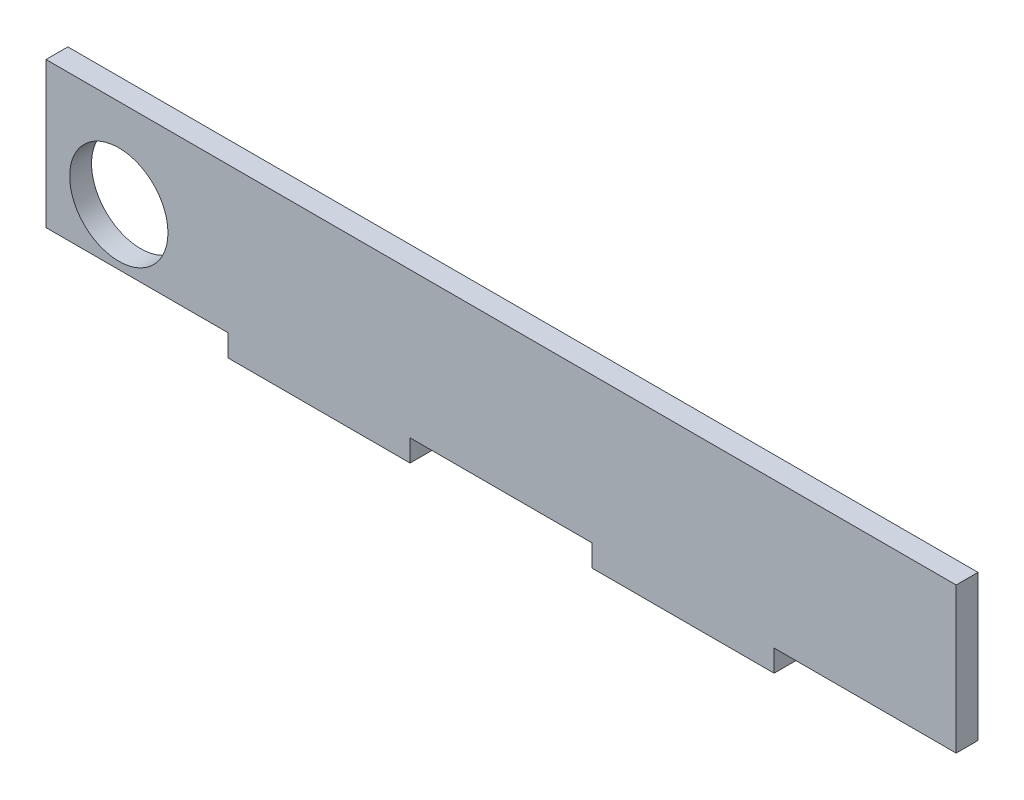
SolidWorks part; units mm, degrees
material "Pine"
ref_plane "Front Plane" through (0, 0, 0) normal (0, 0, 1) x (1, 0, 0)
ref_plane "Top Plane" through (0, 0, 0) normal (0, 1, 0) x (1, 0, 0)
ref_plane "Right Plane" through (0, 0, 0) normal (1, 0, 0) x (0, 0, -1)
sketch "Sketch1" plane through (0, 0, 0) normal (0, 0, 1) x (1, 0, 0)
  line L1 (-125, 23) -> (125, 23)
  line L2 (-125, 23) -> (-125, -23)
  line L3 (-125, -23) -> (125, -23)
  line L4 (125, 23) -> (125, -23)
  line L5 (-125, 23) -> (125, -23) construction
  line L6 (-125, -23) -> (125, 23) construction
  point P0 (0, 0)
  dimension "D1" = 46
  dimension "D2" = 250
extrude "Boss-Extrude1" add sketch "Sketch1" along normal blind 6
sketch "Sketch2" plane through (0, 0, 6) normal (0, 0, 1) x (1, 0, 0)
  line L0 (-25, -23) -> (-25, -17)
  line L1 (-125, -23) -> (-75, -23)
  line L2 (-125, -23) -> (-125, -17)
  line L3 (-125, -17) -> (-75, -17)
  line L4 (-75, -23) -> (-75, -17)
  line L5 (-25, -23) -> (25, -23)
  line L6 (25, -23) -> (25, -17)
  line L7 (-25, -17) -> (25, -17)
  line L8 (75, -23) -> (75, -17)
  line L9 (75, -23) -> (125, -23)
  line L10 (125, -23) -> (125, -17)
  line L11 (75, -17) -> (125, -17)
  dimension "D1" = 50
  dimension "D2" = 6
  dimension "D3" = 3
extrude "Cut-Extrude1" cut sketch "Sketch2" against normal blind 6
sketch "Sketch3" plane through (0, 0, 6) normal (0, 0, 1) x (1, 0, 0)
  line L0 (-125, 23) -> (-125, -17) construction
  line L1 (-75, -17) -> (-125, -17) construction
  circle A0 centre (-105, -1.5) radius 13.5
  dimension "D1" = 27
  dimension "D2" = 20
  dimension "D3" = 15.5
extrude "Cut-Extrude2" cut sketch "Sketch3" against normal blind 10
